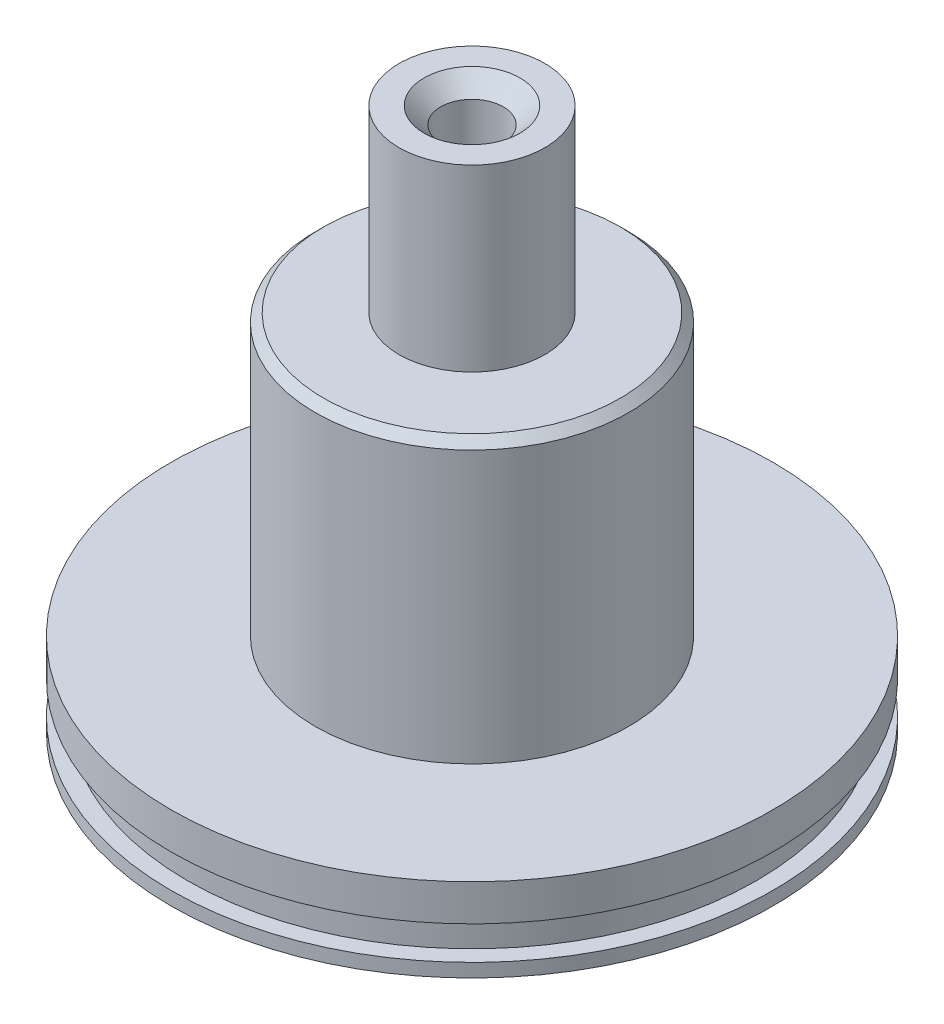
SolidWorks part; units mm, degrees
material "1060 Alloy"
ref_plane "Front Plane" through (0, 0, 0) normal (0, 0, 1) x (1, 0, 0)
ref_plane "Top Plane" through (0, 0, 0) normal (0, 1, 0) x (1, 0, 0)
ref_plane "Right Plane" through (0, 0, 0) normal (1, 0, 0) x (0, 0, -1)
sketch "Sketch1" plane through (0, 0, 0) normal (0, 1, 0) x (1, 0, 0)
  circle A0 centre (0, 0) radius 45.847
  dimension "D1" = 91.694
extrude "Boss-Extrude1" add sketch "Sketch1" along normal blind 12.7
sketch "Sketch2" plane through (0, 12.7, 0) normal (0, 1, 0) x (1, 0, 0)
  circle A0 centre (0, 0) radius 23.876
  dimension "D1" = 47.752
extrude "Boss-Extrude2" add sketch "Sketch2" along normal blind 42.672
sketch "Sketch3" plane through (0, 55.372, 0) normal (0, 1, 0) x (1, 0, 0)
  circle A0 centre (0, 0) radius 11.1125
  dimension "D1" = 22.225
extrude "Boss-Extrude3" add sketch "Sketch3" along normal blind 27.305
sketch "Sketch5" plane through (0, 82.677, 0) normal (0, 1, 0) x (1, 0, 0)
  circle A0 centre (0, 0) radius 4.7625
  dimension "D1" = 9.525
extrude "Cut-Extrude1" cut sketch "Sketch5" against normal blind 25.4
chamfer "Chamfer1" distance 2.54 angle 45 1 edges at (0, 82.677, 4.7625)
chamfer "Chamfer2" distance 1.27 angle 45 1 edges at (0, 55.372, 23.876)
sketch "Sketch6" plane through (0, 0, 0) normal (0, -1, 0) x (1, 0, 0)
  circle A0 centre (0, 0) radius 19.05
  dimension "D1" = 38.1
extrude "Cut-Extrude2" cut sketch "Sketch6" against normal blind 50.8
sketch "Sketch7" plane through (0, 0, 0) normal (0, -1, 0) x (1, 0, 0)
  circle A0 centre (0, 0) radius 45.847 construction
  circle A1 centre (0, 0) radius 45.847
  circle A2 centre (0, 0) radius 43.307
  dimension "D1" = 2.54
extrude "Cut-Extrude3" cut sketch "Sketch7" against normal blind 5.08 from offset 2.0574
